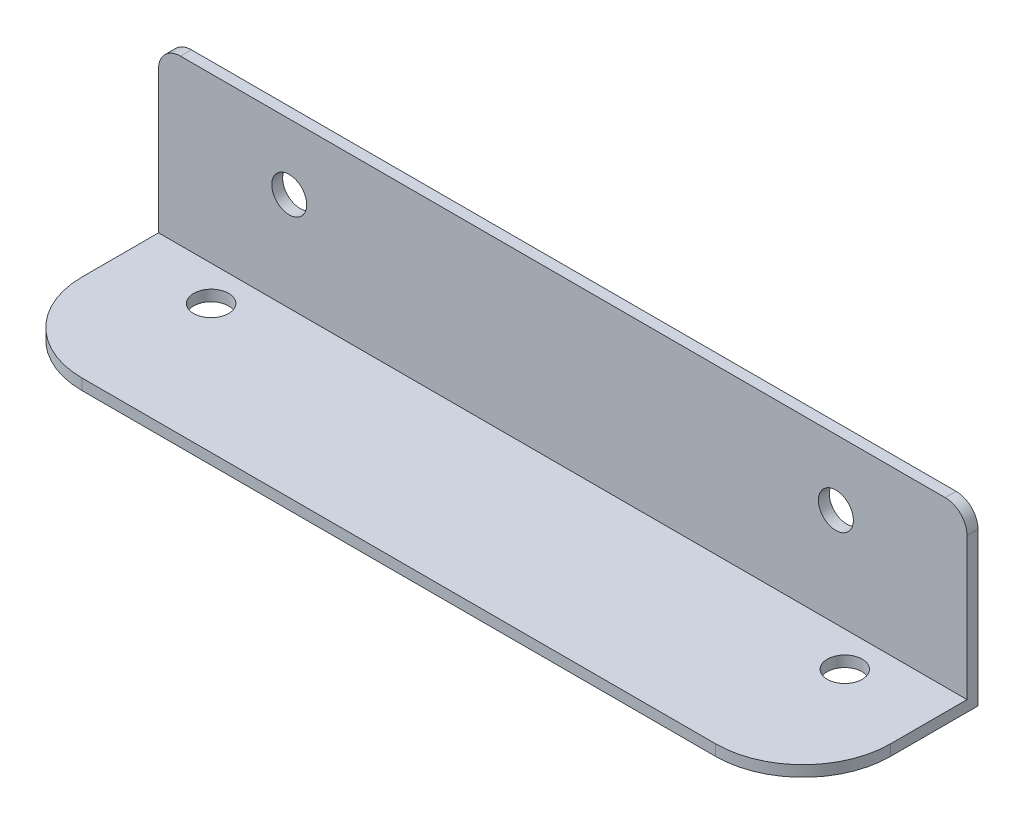
SolidWorks part; units mm, degrees
ref_plane "Front Plane" through (0, 0, 0) normal (0, 0, 1) x (1, 0, 0)
ref_plane "Top Plane" through (0, 0, 0) normal (0, 1, 0) x (1, 0, 0)
ref_plane "Right Plane" through (0, 0, 0) normal (1, 0, 0) x (0, 0, -1)
sketch "Sketch1" plane through (0, 0, 0) normal (0, 0, 1) x (1, 0, 0)
  line L1 (0, 12.7) -> (117.4, 12.7)
  line L2 (0, 12.7) -> (0, -12.7)
  line L3 (0, -12.7) -> (117.4, -12.7)
  line L4 (117.4, 12.7) -> (117.4, -12.7)
  dimension "D1" = 0
  dimension "D2" = 117.4
  dimension "D3" = 12.7
  dimension "D4" = 12.7
extrude "Boss-Extrude1" add sketch "Sketch1" along normal blind 1.5875
sketch "Sketch2" plane through (0, 0, 1.5875) normal (0, 0, 1) x (1, 0, 0)
  line L0 (117.4, -12.7) -> (117.4, 12.7) construction
  line L1 (0, -12.7) -> (117.4, -12.7)
  line L2 (0, -12.7) -> (0, -11.1125)
  line L3 (0, -11.1125) -> (117.4, -11.1125)
  line L4 (117.4, -12.7) -> (117.4, -11.1125)
  dimension "D1" = 1.5875
extrude "Boss-Extrude2" add sketch "Sketch2" along normal blind 23.8125
sketch "Sketch3" plane through (0, -11.1125, 0) normal (0, 1, 0) x (1, 0, 0)
  line L0 (0, -25.4) -> (0, -1.5875) construction
  line L2 (0, 0) -> (117.4, 0) construction
  circle A0 centre (12.7, -6.6484) radius 2.54
  circle A1 centre (104.699, -6.6484) radius 2.54
  dimension "D5" = 5.08
  dimension "D6" = 5.08
  dimension "D1" = 12.7
  dimension "D2" = 91.999
  dimension "D3" = 6.6484
  dimension "D4" = 0
extrude "Cut-Extrude1" cut sketch "Sketch3" against normal up to surface (1.5875 mm away) up to face at (58.7, -12.7, 12.7)
sketch "Sketch4" plane through (0, 0, 1.5875) normal (0, 0, 1) x (1, 0, 0)
  line L0 (117.4, 12.7) -> (0, 12.7) construction
  line L2 (117.4, -11.1125) -> (117.4, 12.7) construction
  circle A0 centre (18.975, 3.175) radius 2.54
  circle A1 centre (98.35, 3.175) radius 2.54
  dimension "D2" = 5.08
  dimension "D6" = 5.08
  dimension "D1" = 9.525
  dimension "D3" = 79.375
  dimension "D4" = 19.05
  dimension "D5" = 0
extrude "Cut-Extrude2" cut sketch "Sketch4" against normal up to surface (1.5875 mm away) up to face at (58.7, 0, 0)
fillet "Fillet1" radius 12.7 2 edges at (117.4, -11.9062, 25.4) (0, -11.9062, 25.4)
fillet "Fillet2" radius 3.175 2 edges at (117.4, 12.7, 0.7937) (0, 12.7, 0.7937)
